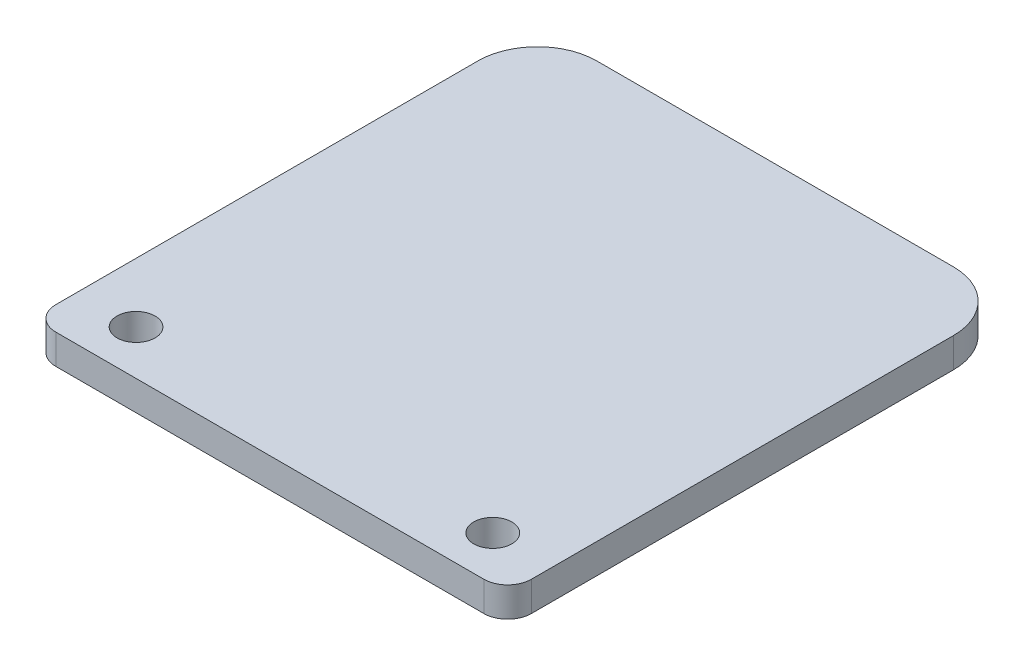
SolidWorks part; units mm, degrees
ref_plane "Front Plane" through (0, 0, 0) normal (0, 0, 1) x (1, 0, 0)
ref_plane "Top Plane" through (0, 0, 0) normal (0, 1, 0) x (1, 0, 0)
ref_plane "Right Plane" through (0, 0, 0) normal (1, 0, 0) x (0, 0, -1)
sketch "Sketch1" plane through (0, 0, 0) normal (0, 1, 0) x (1, 0, 0)
  line L1 (-25.4, 26.9875) -> (25.4, 26.9875)
  line L2 (-25.4, 26.9875) -> (-25.4, -26.9875)
  line L3 (-25.4, -26.9875) -> (25.4, -26.9875)
  line L4 (25.4, 26.9875) -> (25.4, -26.9875)
  line L5 (-25.4, 26.9875) -> (25.4, -26.9875) construction
  line L6 (-25.4, -26.9875) -> (25.4, 26.9875) construction
  point P0 (0, 0)
  dimension "D1" = 50.8
  dimension "D2" = 53.975
extrude "Boss-Extrude1" add sketch "Sketch1" along normal blind 3.175
sketch "Sketch2" plane through (0, 0, 0) normal (0, -1, 0) x (-1, 0, 0)
  line L0 (25.4, -26.9875) -> (-25.4, -26.9875) construction
  line L1 (-19.05, -22.225) -> (-25.4, -22.225) construction
  line L2 (-25.4, -26.9875) -> (-25.4, 26.9875) construction
  line L3 (19.05, -22.225) -> (25.4, -22.225) construction
  line L4 (25.4, 26.9875) -> (25.4, -26.9875) construction
  circle A0 centre (-19.05, -22.225) radius 2.032
  circle A1 centre (19.05, -22.225) radius 2.032
  dimension "D2" = 4.064
  dimension "D1" = 4.7625
  dimension "D3" = 38.1
extrude "Cut-Extrude1" cut sketch "Sketch2" against normal through all
fillet "Fillet1" radius 2.54 2 edges at (-25.4, 1.5875, 26.9875) (25.4, 1.5875, 26.9875)
fillet "Fillet2" radius 6.35 2 edges at (25.4, 1.5875, -26.9875) (-25.4, 1.5875, -26.9875)
